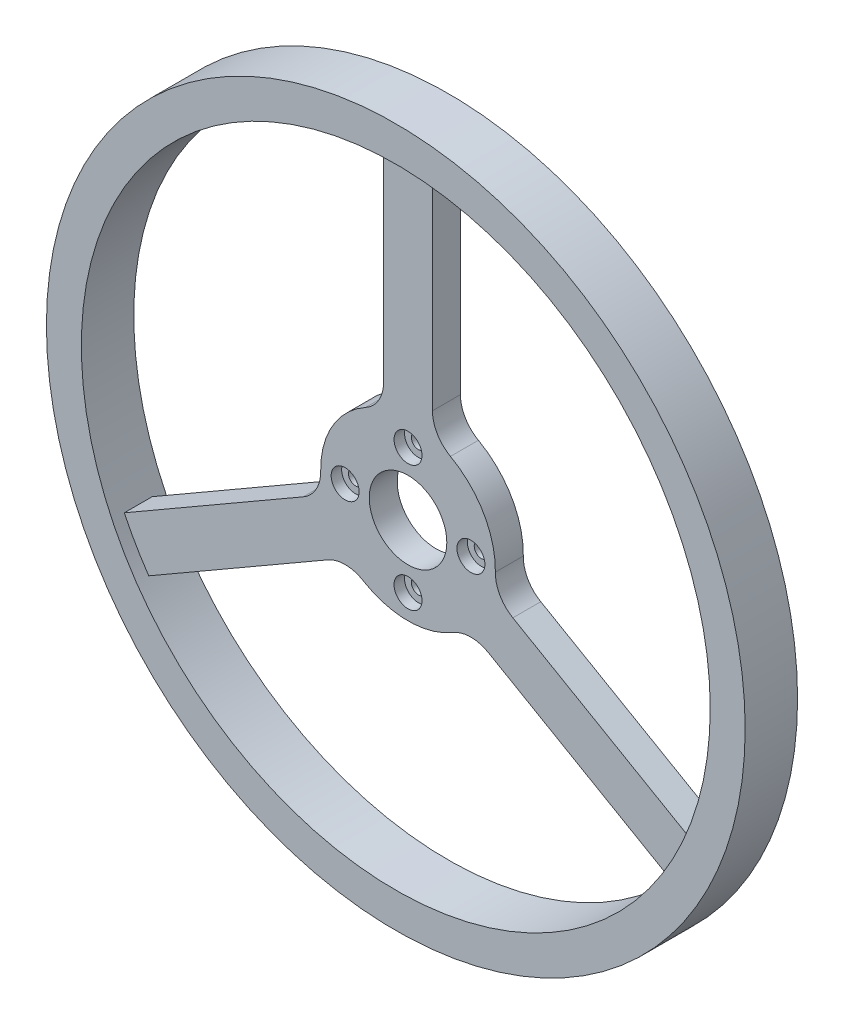
SolidWorks part; units mm, degrees
ref_plane "Front Plane" through (0, 0, 0) normal (0, 0, 1) x (1, 0, 0)
ref_plane "Top Plane" through (0, 0, 0) normal (0, 1, 0) x (1, 0, 0)
ref_plane "Right Plane" through (0, 0, 0) normal (1, 0, 0) x (0, 0, -1)
sketch "Sketch1" plane through (0, 0, 0) normal (0, 0, 1) x (1, 0, 0)
  circle A0 centre (0, 0) radius 100
  dimension "D1" = 200
extrude "Boss-Extrude1" add sketch "Sketch1" along normal blind 15
sketch "Sketch2" plane through (0, 0, 0) normal (0, 0, 1) x (1, 0, 0)
  circle A0 centre (0, 0) radius 90
  dimension "D1" = 180
extrude "Cut-Extrude1" cut sketch "Sketch2" along normal through all both
sketch "Sketch5" plane through (0, 0, 0) normal (0, 0, 1) x (1, 0, 0)
  circle A0 centre (0, 0) radius 25
  dimension "D1" = 50
extrude "Boss-Extrude3" add sketch "Sketch5" along normal blind 8 from offset 3.5
sketch "Sketch6" plane through (0, 0, 0) normal (0, 0, 1) x (1, 0, 0)
  line L0 (0, 0) -> (-73.8626, -42.6446) construction
  line L1 (0, 0) -> (69.4127, -40.0754) construction
  line L2 (0, -8.25) -> (0, 8.25) construction
  line L3 (-7, 24) -> (7, 24)
  line L4 (7, 24) -> (7, 94)
  line L5 (7, 94) -> (-7, 94)
  line L6 (-7, 94) -> (-7, 24)
  line L8 (17.2846, -18.0622) -> (77.9064, -53.0622)
  line L9 (77.9064, -53.0622) -> (84.9064, -40.9378)
  line L10 (84.9064, -40.9378) -> (24.2846, -5.9378)
  line L12 (24.2846, -5.9378) -> (17.2846, -18.0622)
  line L14 (-17.2846, -18.0622) -> (-77.9064, -53.0622)
  line L15 (-77.9064, -53.0622) -> (-84.9064, -40.9378)
  line L16 (-84.9064, -40.9378) -> (-24.2846, -5.9378)
  line L18 (-24.2846, -5.9378) -> (-17.2846, -18.0622)
  circle A0 centre (0, 0) radius 25 construction
  point P9 (0, 0)
  point P21 (0, 0)
  point P22 (0, 0)
  point P23 (0, 0)
  point P24 (0, 0)
  dimension "D1" = 120
  dimension "D2" = 120
  dimension "D3" = 70
  dimension "D4" = 70
  dimension "D5" = 70
  dimension "D6" = 14
  dimension "D7" = 14
  dimension "D8" = 14
  dimension "D9" = 7
  dimension "D10" = 7
  dimension "D11" = 7
extrude "Boss-Extrude4" add sketch "Sketch6" along normal blind 8 from offset 3.5
sketch "Sketch9" plane through (0, 0, 0) normal (0, 0, 1) x (1, 0, 0)
  circle A0 centre (0, 0) radius 11.1
  dimension "D1" = 22.2
extrude "Cut-Extrude4" cut sketch "Sketch9" along normal through all
sketch "Sketch10" plane through (0, 0, 0) normal (0, 0, 1) x (1, 0, 0)
  line L0 (0, -8.25) -> (0, 8.25) construction
  line L1 (8.25, 0) -> (-8.25, 0) construction
  circle A0 centre (0, 18) radius 2.05
  circle A1 centre (18, 0) radius 2.05
  circle A2 centre (0, -18) radius 2.05
  circle A3 centre (-18, 0) radius 2.05
  dimension "D5" = 4.1
  dimension "D1" = 18
  dimension "D2" = 18
  dimension "D3" = 18
  dimension "D4" = 18
extrude "Cut-Extrude5" cut sketch "Sketch10" along normal through all
fillet "Fillet3" radius 10 6 edges at (7, 24, 7.5) (24.2846, -5.9378, 7.5) (17.2846, -18.0622, 7.5) (-17.2846, -18.0622, 7.5) (-24.2846, -5.9378, 7.5) (-7, 24, 7.5)
sketch "Sketch11" plane through (0, 0, 0) normal (0, 0, 1) x (1, 0, 0)
  circle A0 centre (18, 0) radius 4
  circle A1 centre (0, -18) radius 4
  circle A2 centre (-18, 0) radius 4
  circle A3 centre (0, 18) radius 4
  dimension "D1" = 8
extrude "Cut-Extrude6" cut sketch "Sketch11" against normal blind 3 from surface
